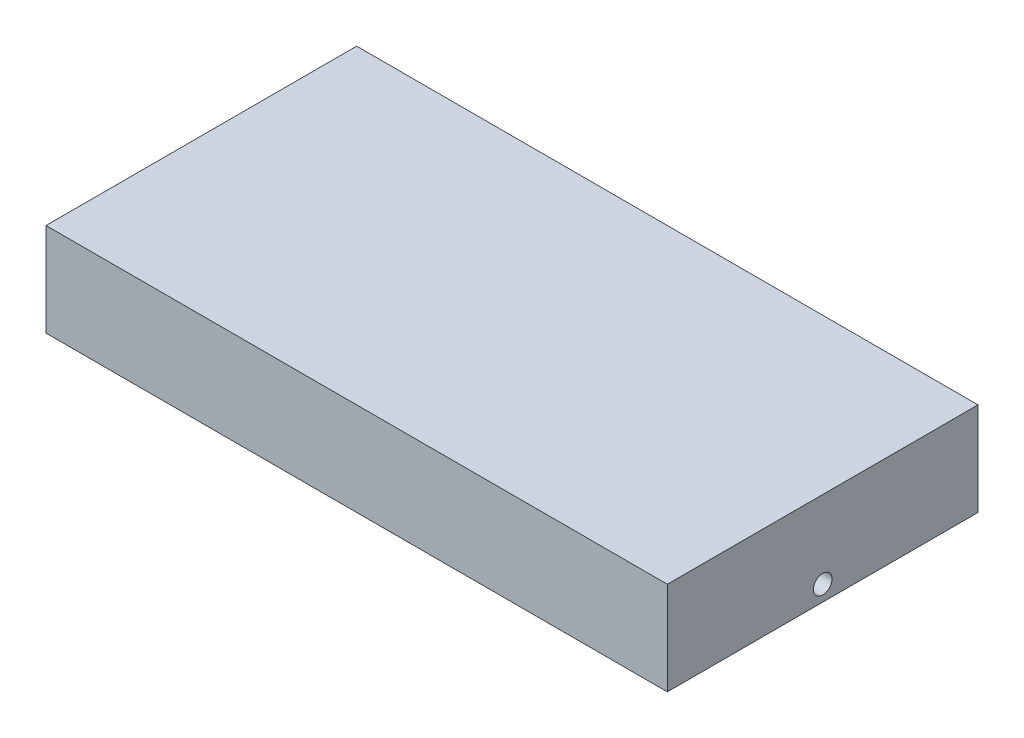
SolidWorks part; units mm, degrees
ref_plane "前视基准面" through (0, 0, 0) normal (0, 0, 1) x (1, 0, 0)
ref_plane "上视基准面" through (0, 0, 0) normal (0, 1, 0) x (1, 0, 0)
ref_plane "右视基准面" through (0, 0, 0) normal (1, 0, 0) x (0, 0, -1)
sketch "草图1" plane through (0, 0, 0) normal (0, 1, 0) x (1, 0, 0)
  line L1 (-10, 5) -> (10, 5)
  line L2 (-10, 5) -> (-10, -5)
  line L3 (-10, -5) -> (10, -5)
  line L4 (10, 5) -> (10, -5)
extrude "凸台-拉伸1" add sketch "草图1" along normal blind 3
sketch "草图2" plane through (0, 0, 0) normal (0, 1, 0) x (1, 0, 0)
  line L1 (-8, 3) -> (8, 3)
  line L2 (-8, 3) -> (-8, -3)
  line L3 (-8, -3) -> (8, -3)
  line L4 (8, 3) -> (8, -3)
extrude "切除-拉伸1" cut sketch "草图2" along normal blind 2
sketch "草图3" plane through (-8, 0, 0) normal (1, 0, 0) x (0, 0, -1)
  line L0 (3, 2) -> (3, 0) construction
  line L1 (-3, 1.3) -> (3, 1.3)
  line L2 (-3, 1.3) -> (-3, 1.5)
  line L3 (-3, 1.5) -> (3, 1.5)
  line L4 (3, 1.3) -> (3, 1.5)
extrude "切除-拉伸2" cut sketch "草图3" against normal blind 1.5
sketch "草图5" plane through (0, 1.5, 0) normal (0, -1, 0) x (1, 0, 0)
  line L1 (-8.2, 3) -> (-9.5, 3)
  line L2 (-8.2, 3) -> (-8.2, -3)
  line L3 (-8.2, -3) -> (-9.5, -3)
  line L4 (-9.5, 3) -> (-9.5, -3)
extrude "切除-拉伸4" cut sketch "草图5" along normal blind 1.3
sketch "草图11" plane through (-10, 0, 0) normal (-1, 0, 0) x (0, 0, 1)
  circle A0 centre (0, 0.5) radius 0.3
extrude "切除-拉伸7" cut sketch "草图11" against normal blind 0.5
sketch "草图14" plane through (0, 0, 0) normal (0, -1, 0) x (1, 0, 0)
  line L1 (8.1, 3) -> (9.5, 3)
  line L2 (8.1, 3) -> (8.1, -3)
  line L3 (8.1, -3) -> (9.5, -3)
  line L4 (9.5, 3) -> (9.5, -3)
extrude "切除-拉伸9" cut sketch "草图14" against normal blind 1.5
sketch "草图15" plane through (10, 0, 0) normal (1, 0, 0) x (0, 0, -1)
  circle A0 centre (0, 0.5) radius 0.3
extrude "切除-拉伸10" cut sketch "草图15" against normal blind 0.5
